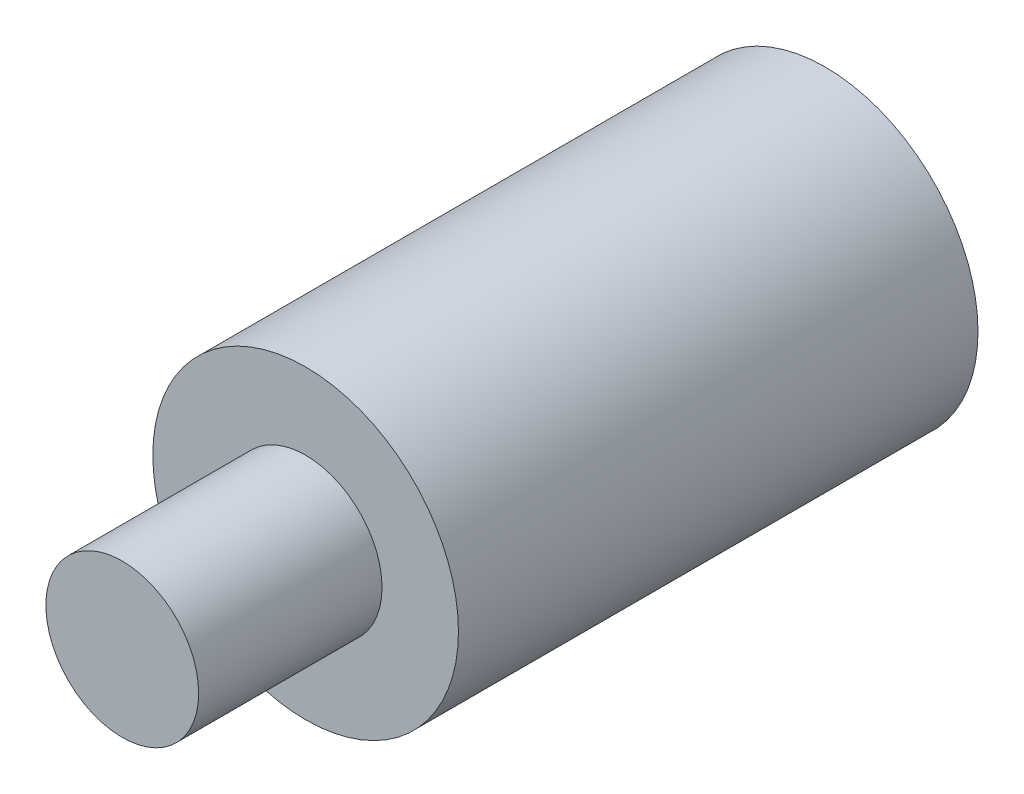
SolidWorks part; units mm, degrees
ref_plane "Alzado" through (0, 0, 0) normal (0, 0, 1) x (1, 0, 0)
ref_plane "Planta" through (0, 0, 0) normal (0, 1, 0) x (1, 0, 0)
ref_plane "Vista lateral" through (0, 0, 0) normal (1, 0, 0) x (0, 0, -1)
sketch "Croquis1" plane through (0, 0, 0) normal (0, 0, 1) x (1, 0, 0)
  circle A0 centre (0, 0) radius 10
  dimension "D1" = 20
extrude "Saliente-Extruir1" add sketch "Croquis1" along normal blind 34
sketch "Croquis2" plane through (0, 0, 34) normal (0, 0, 1) x (1, 0, 0)
  circle A0 centre (0, 0) radius 5
  dimension "D1" = 10
extrude "Saliente-Extruir2" add sketch "Croquis2" along normal blind 12
